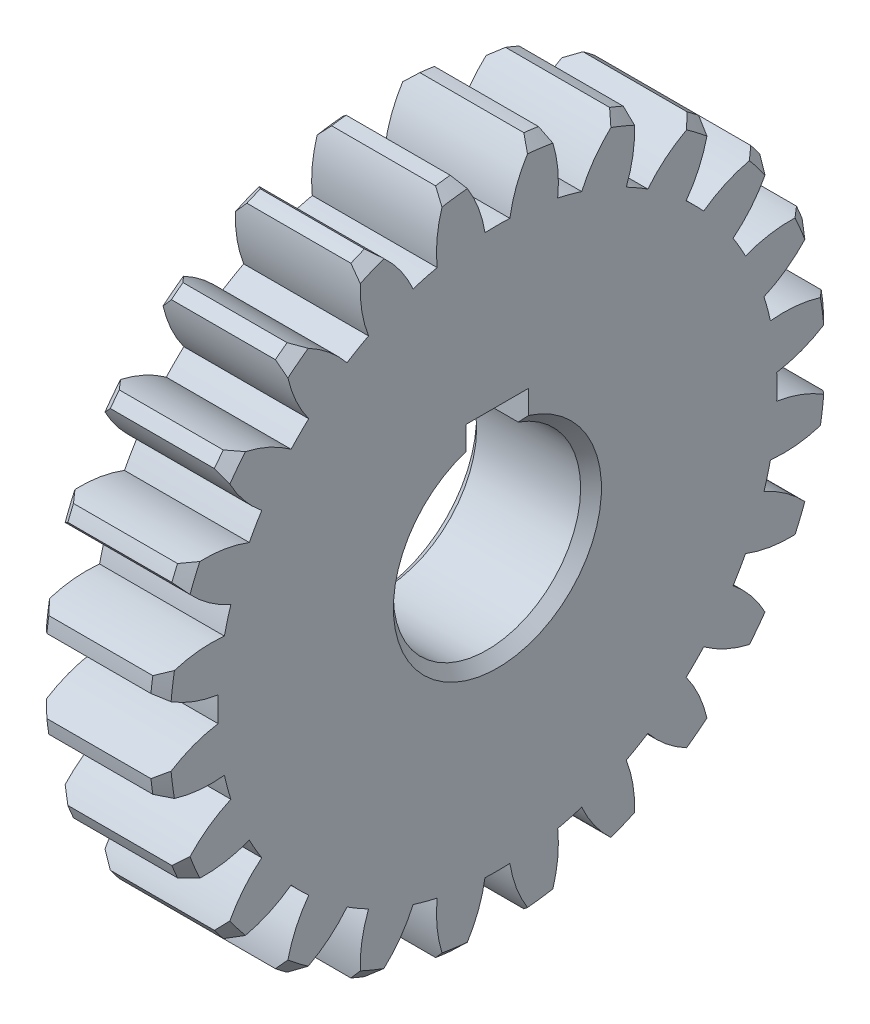
SolidWorks part; units mm, degrees
ref_plane "Plane1" through (0, 0, 0) normal (0, 0, 1) x (1, 0, 0)
ref_plane "Plane2" through (0, 0, 0) normal (0, 1, 0) x (1, 0, 0)
ref_plane "Plane3" through (0, 0, 0) normal (1, 0, 0) x (0, 0, -1)
sketch "HoldingSke" plane through (0, 0, 0) normal (0, 1, 0) x (1, 0, 0)
  line L0 (0, 0) -> (0.3654, -0.1627)
  line L1 (-15, 0) -> (100, 0) construction
  line L2 (0, 0) -> (-2.1039, 2.3779)
  line L3 (0, 0) -> (-11.863, 4.5341)
  line L4 (0, 0) -> (7.8894, 3.5126)
  line L5 (0, 0) -> (-46.8476, -17.4728)
  line L6 (0, 0) -> (-9.9476, -6.7116)
  line L7 (-2.1039, 2.3779) -> (8.6586, 51.2059)
  line L8 (-76.2, 54.61) -> (-73.4, 54.61)
  line L9 (-71.009, 38.7566) -> (-53.1078, 45.2721)
  line L10 (-76.2, 71.12) -> (104.1128, 71.12)
  line L11 (0, 0) -> (-12, 0)
  line L12 (-76.2, 101.6) -> (-76.113, 101.6)
  line L13 (24.9733, 27.94) -> (52.9518, 28.4284)
  line L14 (24.9733, 27.94) -> (24.9743, 27.94)
  line L15 (24.9733, 27.94) -> (100.4006, 29.5858)
  line L16 (-63.627, -2.5) -> (-12.827, -2.5)
  circle A0 centre (0, 0) radius 9
  circle A1 centre (0, 0) radius 26.874
  circle A2 centre (0, 0) radius 37.5
  circle A3 centre (0, 0) radius 9
  dimension "MHD" = 53.748
  dimension "Hub_dia" = 75
  dimension "Bore" = 18
  dimension "MBD" = 18
  dimension "Num_teeth" = 24
  dimension "Pitch" = 0.4
  dimension "Overall_len" = 50
  dimension "Show_teeth" = 24
  dimension "Thickness" = 12
  dimension "OAL" = 50.0001
  dimension "T_dim" = 2.8
  dimension "Ap" = 20
  dimension "H" = 19.05
  dimension "Pitch_radius" = 180.3128
  dimension "Width" = 12
  dimension "Backlash" = 0.087
  dimension "Addendum_fac" = 1
  dimension "Dedendum_fac" = 1.25
  dimension "Clearance_fac" = 0.25
  dimension "Dedendum_add" = 0.001
  dimension "Module" = 2.5
sketch "BasProSke" plane through (0, 0, 0) normal (0, 1, 0) x (1, 0, 0)
  line L0 (-10, 0) -> (60, 0) construction
  line L1 (0, 0) -> (0, 32.5)
  line L2 (0, 0) -> (12, 0)
  line L3 (12, 0) -> (12, 32.5)
  line L4 (12, 32.5) -> (0, 32.5)
  dimension "Thickness" = 12
  dimension "Diameter" = 65
revolve "Base-Revolve" add sketch "BasProSke" angle 360 about L0
sketch "TooCutSke" plane through (0, 0, 0) normal (1, 0, 0) x (0, 0, -1)
  line L1 (0, 0) -> (0, 107) construction
  line L2 (0, 0) -> (-2.1143, 29.9254) construction
  line L3 (0, 0) -> (-7.8173, 59.3783) construction
  line L4 (-2.1143, 29.9254) -> (-3.9087, 29.6892) construction
  arc A0 (1.1963, 26.8474) -> (-1.1963, 26.8474) centre (0, 0) ccw
  arc A1 (3.5598, 32.33) -> (-3.5598, 32.33) centre (0, 0) ccw
  circle A2 centre (0, 0) radius 30 construction
  circle A3 centre (0, 0) radius 28.1908 construction
  arc A4 (-1.1963, 26.8474) -> (-3.5598, 32.33) centre (-13.0513, 24.9877) ccw
  arc A5 (3.5598, 32.33) -> (1.1963, 26.8474) centre (13.0513, 24.9877) ccw
  dimension "Root_dia" = 53.748
  dimension "Overcut_dia" = 65.0508
  dimension "Pitch_dia" = 60
  dimension "Base_dia" = 56.3816
  dimension "Flank_rad" = 12
  dimension "Half_ang" = 7.5
  dimension "Half_CT" = 1.8098
extrude "ToothCut" cut sketch "TooCutSke" along normal through all
fillet "Breaks" [suppressed] radius 0.05
fillet "RootFillets" [suppressed] radius 0.626
pattern_circular "TeethCuts" count 24 every 15 about axis through (-10, 0, 0) along (1, 0, 0) of "ToothCut", "RootFillets", "Breaks"
sketch "HubNeaOneSke" plane through (0, 0, 0) normal (-1, 0, 0) x (0, 0, 1)
  circle A0 centre (0, 0) radius 26.874
  dimension "Diameter" = 53.748
extrude "HubNearOne" [suppressed] add sketch "HubNeaOneSke" along normal blind 38.0001
sketch "HubNeaBotSke" plane through (0, 0, 0) normal (-1, 0, 0) x (0, 0, 1)
  circle A0 centre (0, 0) radius 26.874
  dimension "Diameter" = 53.748
extrude "HubNearBoth" [suppressed] add sketch "HubNeaBotSke" along normal blind 19
ref_plane "FarPln" through (12, 0, 0) normal (1, 0, 0) x (0, 0, -1)
sketch "HubFarSke" plane through (12, 0, 0) normal (1, 0, 0) x (0, 0, -1)
  circle A0 centre (0, 0) radius 26.874
  dimension "Diameter" = 53.748
extrude "HubFar" [suppressed] add sketch "HubFarSke" along normal blind 19
sketch "BorSke" plane through (0, 0, 0) normal (1, 0, 0) x (0, 0, -1)
  circle A0 centre (0, 0) radius 9
  dimension "Diameter" = 18
extrude "Bore" cut sketch "BorSke" along normal mid plane 100.0001
sketch "KeySke" plane through (0, 0, 0) normal (1, 0, 0) x (0, 0, -1)
  line L0 (-3, 0) -> (-3, 11.8)
  line L1 (-3, 11.8) -> (3, 11.8)
  line L2 (3, 11.8) -> (3, 0)
  line L3 (0, 0) -> (0, 34) construction
  line L4 (-3, 0) -> (3, 0)
  dimension "Offset" = 11.8
  dimension "Width" = 6
extrude "Keyway" cut sketch "KeySke" along normal mid plane 100.0001
pattern_circular "Keyway2" [suppressed] count 2 every 90 about axis through (-10, 0, 0) along (1, 0, 0)
chamfer "Chamfer1" distance 1 angle 45 50 edges at (12, -9, 0) (0, 30.0261, 12.4372) (0, 25.784, 19.7847) (0, 19.7847, 25.784) (0, 12.4372, 30.0261) (0, 4.2421, 32.222) (0, -4.2421, 32.222) (0, -12.4372, 30.0261) (0, -19.7847, 25.784) (0, -25.784, 19.7847) (0, -30.0261, 12.4372) (0, -32.222, 4.2421) (0, -32.222, -4.2421) (0, -30.0261, -12.4372) (0, -25.784, -19.7847) (0, -19.7847, -25.784) (0, -12.4372, -30.0261) (0, -4.2421, -32.222) (0, 4.2421, -32.222) (0, 12.4372, -30.0261) (0, 19.7847, -25.784) (0, 25.784, -19.7847) (0, 30.0261, -12.4372) (0, 32.222, -4.2421) (0, 32.222, 4.2421) (12, 19.7847, -25.784) (12, 25.784, -19.7847) (12, 30.0261, -12.4372) (12, 32.222, -4.2421) (12, 32.222, 4.2421) (12, 30.0261, 12.4372) (12, 12.4372, -30.0261) (12, 4.2421, -32.222) (12, -4.2421, -32.222) (12, -12.4372, -30.0261) (12, -19.7847, -25.784) (12, -25.784, -19.7847) (12, -30.0261, -12.4372) (12, -32.222, -4.2421) (12, -32.222, 4.2421) (12, -30.0261, 12.4372) (12, -25.784, 19.7847) (12, -19.7847, 25.784) (12, -12.4372, 30.0261) (12, -4.2421, 32.222) (12, 4.2421, 32.222) (12, 12.4372, 30.0261) (12, 19.7847, 25.784) (12, 25.784, 19.7847) (0, -9, 0)
equation "' \"Module@HoldingSke\" = 6.35"
equation "' \"Num_teeth@HoldingSke\" = 12"
equation "' \"Ap@HoldingSke\" =  20"
equation "' \"Ap@HoldingSke\" = 20"
equation "' \"Width@HoldingSke\" = 0.5 * 25.4"
equation "' \"Hub_dia@HoldingSke\"= 1 * 25.4"
equation "' \"Hub_dia@HoldingSke\" = 1 * 25.4"
equation "' \"Overall_len@HoldingSke\" = 1.0 * 25.4"
equation "' \"Bore@HoldingSke\" = 0.75 * 25.4"
equation "' \"T_dim@HoldingSke\" = 0.1 * 25.4"
equation "' \"Width@KeySke\" = 0.25 * 25.4"
equation "' \"Show_teeth@HoldingSke\" = 13"
equation "' \"Backlash@HoldingSke\" = 0.009 * 25.4"
equation "' \"Addendum_fac@HoldingSke\" = 1.0"
equation "' \"Dedendum_fac@HoldingSke\" = 1.25"
equation "' \"Dedendum_add@HoldingSke\" = 0.00005 * 25.4"
equation "' \"Clearance_fac@HoldingSke\" = 0.25"
equation "\"Pitch@HoldingSke\" = 1 / \"Module@HoldingSke\""
equation "\"Overcut_dia@TooCutSke\" = (\"Num_teeth@HoldingSke\" + 2 * \"Addendum_fac@HoldingSke\") / \"Pitch@HoldingSke\" + 0.002 * 25.4"
equation "\"Pitch_dia@TooCutSke\" = \"Num_teeth@HoldingSke\" / \"Pitch@HoldingSke\""
equation "\"Base_dia@TooCutSke\" = \"Num_teeth@HoldingSke\" / \"Pitch@HoldingSke\" * cos((\"Ap@HoldingSke\"  * 3.14159265 / 180))"
equation "\"Root_dia@TooCutSke\" = (\"Num_teeth@HoldingSke\" + 2) / \"Pitch@HoldingSke\" - 2 * (\"Addendum_fac@HoldingSke\" + \"Dedendum_fac@HoldingSke\") / \"Pitch@HoldingSke\" - \"Dedendum_add@HoldingSke\" * 2"
equation "\"Half_ang@TooCutSke\" = 180 / \"Num_teeth@HoldingSke\""
equation "\"Half_CT@TooCutSke\" = \"Num_teeth@HoldingSke\" / \"Pitch@HoldingSke\" * sin((3.14159265 / 2 / \"Num_teeth@HoldingSke\")) / 2 - 7 * \"Backlash@HoldingSke\" / 4"
equation "\"Flank_rad@TooCutSke\" = \"Num_teeth@HoldingSke\" / \"Pitch@HoldingSke\" / 5"
equation "\"Radius@RootFillets\" = \"Clearance_fac@HoldingSke\" / \"Pitch@HoldingSke\" + \"Dedendum_add@HoldingSke\""
equation "\"Break_rad@Breaks\" = 0.02 / \"Pitch@HoldingSke\""
equation "\"Thickness@HoldingSke\" = \"Width@HoldingSke\""
equation "\"OAL@HoldingSke\" = \"Thickness@HoldingSke\""
equation "\"MHD@HoldingSke\" = (\"Num_teeth@HoldingSke\" + 2) / \"Pitch@HoldingSke\" - 2 * (\"Addendum_fac@HoldingSke\" + \"Dedendum_fac@HoldingSke\")  / \"Pitch@HoldingSke\" - \"Dedendum_add@HoldingSke\" * 2"
equation "\"MBD@HoldingSke\" = (\"Num_teeth@HoldingSke\" + 2) / \"Pitch@HoldingSke\" - 2 * (\"Addendum_fac@HoldingSke\" + \"Dedendum_fac@HoldingSke\")  / \"Pitch@HoldingSke\" - \"Dedendum_add@HoldingSke\" * 2 - 0.002 * 25.4"
equation "\"MHD@HoldingSke\" = ((sgn( \"MHD@HoldingSke\" - \"Hub_dia@HoldingSke\" )-1)*( \"MHD@HoldingSke\" - \"Hub_dia@HoldingSke\" ))/-2+ \"Hub_dia@HoldingSke\""
equation "\"MBD@HoldingSke\" = ((sgn( \"MBD@HoldingSke\" - \"Bore@HoldingSke\" )-1)*( \"MBD@HoldingSke\" - \"Bore@HoldingSke\" ))/-2+ \"Bore@HoldingSke\""
equation "\"OAL@HoldingSke\" = ((sgn( \"OAL@HoldingSke\" - \"Overall_len@HoldingSke\" )+1)*( \"OAL@HoldingSke\" - \"Overall_len@HoldingSke\" ))/2 + \"Overall_len@HoldingSke\" + 0.000002 * 25.4"
equation "\"Num_teeth@TeethCuts\" = int( \"Show_teeth@HoldingSke\" ) + 1"
equation "\"Num_teeth@TeethCuts\" = ((sgn( \"Num_teeth@TeethCuts\" - \"Num_teeth@HoldingSke\" )-1)*( \"Num_teeth@TeethCuts\" - \"Num_teeth@HoldingSke\" ))/-2+ \"Num_teeth@HoldingSke\""
equation "\"Num_teeth@TeethCuts\" = ((sgn( \"Num_teeth@TeethCuts\" - 2.0)+1)*( \"Num_teeth@TeethCuts\" - 2.0))/2 +2.0"
equation "\"Angle@TeethCuts\" = 360.0 / \"Num_teeth@HoldingSke\""
equation "\"Diameter@BasProSke\" = (\"Num_teeth@HoldingSke\" + 2 * \"Addendum_fac@HoldingSke\") / \"Pitch@HoldingSke\""
equation "\"Thickness@BasProSke\"  = \"Thickness@HoldingSke\""
equation "' \"Fillet_rad@BasProSke\" =  \"Thickness@HoldingSke\" * 0.05"
equation "' \"Fillet_rad@BasProSke\" = \"Thickness@HoldingSke\" * 0.05"
equation "\"MHD@HoldingSke\" = ((sgn( \"MHD@HoldingSke\" - \"Root_dia@TooCutSke\" )-1)*( \"MHD@HoldingSke\" - \"Root_dia@TooCutSke\" ))/-2+ \"Root_dia@TooCutSke\""
equation "\"Diameter@HubNeaOneSke\" = \"MHD@HoldingSke\""
equation "\"Length@HubNearOne\" = \"OAL@HoldingSke\" - \"Thickness@BasProSke\""
equation "\"Diameter@HubNeaBotSke\" = \"MHD@HoldingSke\""
equation "\"Length@HubNearBoth\" = ( \"OAL@HoldingSke\" - \"Thickness@BasProSke\" ) / 2.0"
equation "\"Thickness@FarPln\" = \"Thickness@BasProSke\""
equation "\"Diameter@HubFarSke\" = \"MHD@HoldingSke\""
equation "\"Length@HubFar\" = ( \"OAL@HoldingSke\" - \"Thickness@BasProSke\" ) / 2.0"
equation "\"Diameter@BorSke\" = \"MBD@HoldingSke\""
equation "\"D1@Bore\" = \"OAL@HoldingSke\" * 2.0"
equation "\"D1@Keyway\" = \"OAL@HoldingSke\" * 2.0"
equation "\"Offset@KeySke\" = \"T_dim@HoldingSke\" + \"MBD@HoldingSke\" / 2.0"
